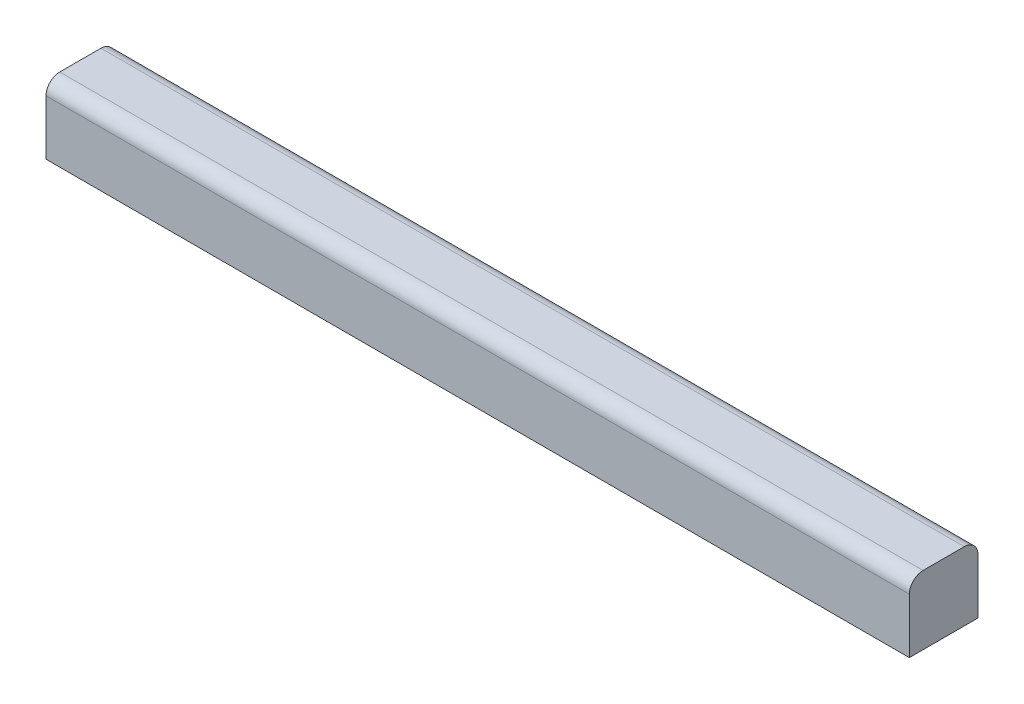
SolidWorks part; units mm, degrees
ref_plane "Front Plane" through (0, 0, 0) normal (0, 0, 1) x (1, 0, 0)
ref_plane "Top Plane" through (0, 0, 0) normal (0, 1, 0) x (1, 0, 0)
ref_plane "Right Plane" through (0, 0, 0) normal (1, 0, 0) x (0, 0, -1)
sketch "Sketch1" plane through (0, 0, 0) normal (0, 0, 1) x (1, 0, 0)
  line L0 (0, 0) -> (0, 21.6484) construction
  line L1 (0, 21.6484) -> (0, -26.0085) construction
  line L2 (-2.8391, 0) -> (-21.6991, 0)
  line L3 (-2.8391, 0) -> (-2.8391, 1.5)
  line L4 (-2.8391, 1.5) -> (-21.6991, 1.5)
  line L5 (-21.6991, 1.5) -> (-21.6991, 0)
  dimension "D1" = 18.86
  dimension "D2" = 1.5
extrude "Boss-Extrude2" add sketch "Sketch1" along normal blind 1.5
fillet "Fillet3" radius 0.3 2 edges at (-12.2691, 1.5, 0) (-12.2691, 1.5, 1.5)
